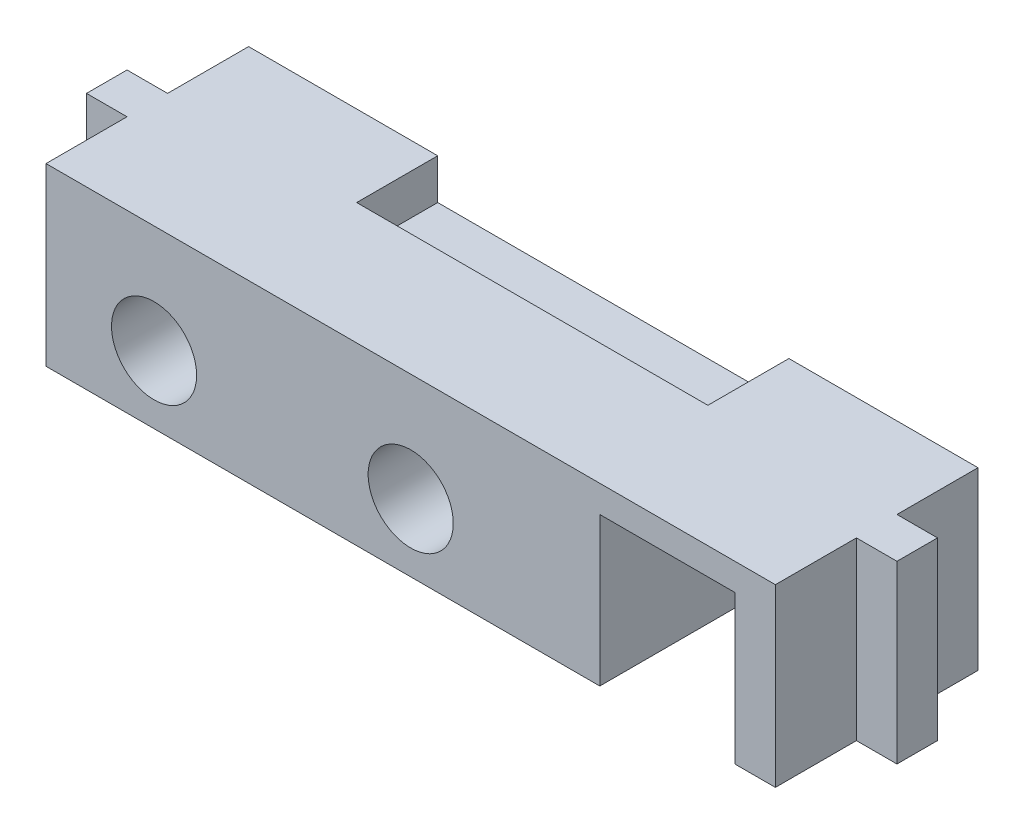
SolidWorks part; units mm, degrees
ref_plane "Front Plane" through (0, 0, 0) normal (0, 0, 1) x (1, 0, 0)
ref_plane "Top Plane" through (0, 0, 0) normal (0, 1, 0) x (1, 0, 0)
ref_plane "Right Plane" through (0, 0, 0) normal (1, 0, 0) x (0, 0, -1)
sketch "Sketch1" plane through (0, 0, 0) normal (0, 0, 1) x (1, 0, 0)
  line L0 (-19, 0) -> (19, 0) construction
  line L3 (-30, -5) -> (-30, 8)
  line L4 (-30, 8) -> (30, 8)
  line L5 (30, -5) -> (30, 8)
  line L6 (-17.2953, -10.5909) -> (25.0889, -10.5909)
  line L7 (-37.5889, -7) -> (12.4111, -7) construction
  line L8 (-37.5889, -7) -> (-37.5889, -5) construction
  line L9 (-37.5889, -5) -> (-13.75, -5) construction
  line L10 (12.4111, -7) -> (12.4111, -5) construction
  line L11 (-37.5889, -7) -> (12.4111, -5) construction
  line L12 (-37.5889, -5) -> (12.4111, -7) construction
  line L14 (14.5, -3) -> (23.5, -3) construction
  line L15 (14.5, -3) -> (14.5, 3) construction
  line L16 (14.5, 3) -> (23.5, 3) construction
  line L17 (23.5, -3) -> (23.5, 3) construction
  line L18 (14.5, -3) -> (23.5, 3) construction
  line L19 (14.5, 3) -> (23.5, -3) construction
  line L23 (-6.25, -5) -> (12.4111, -5) construction
  line L24 (-30, -5) -> (14, -5)
  line L34 (24, -5) -> (24, -6) construction
  line L35 (24, -6) -> (14, -6) construction
  line L36 (24, -5) -> (24, 6)
  line L37 (24, 6) -> (14, 6)
  line L38 (14, -5) -> (14, 6)
  line L39 (24, -6) -> (14, 6) construction
  line L40 (24, 6) -> (14, -6) construction
  line L41 (14, -6) -> (14, -5) construction
  line L42 (24, -5) -> (30, -5)
  circle A0 centre (0, 0) radius 10 construction
  circle A1 centre (19, 0) radius 9 construction
  circle A2 centre (-19, 0) radius 9 construction
  circle A3 centre (19, 0) radius 10.5909 construction
  circle A4 centre (-19, 0) radius 10.5909 construction
  circle A5 centre (0, 0) radius 1.5 construction
  circle A6 centre (-19, 0) radius 3.15
  circle A9 centre (0, 0) radius 3.15
  point P3 (0, 0)
  point P13 (0, 0)
  point P17 (0, 8)
  point P18 (-12.5889, -6)
  point P29 (3.8968, -10.5909)
  dimension "D1" = 20
  dimension "D2" = 18
  dimension "D5" = 3
  dimension "D6" = 10
  dimension "D9" = 6.3
  dimension "D3" = 13
  dimension "D4" = 2
  dimension "D7" = 9
  dimension "D8" = 6
  dimension "D11" = 8
  dimension "D12" = 60
  dimension "D14" = 12
extrude "Boss-Extrude1" add sketch "Sketch1" along normal mid plane 15
sketch "Sketch2" plane through (0, -5, 0) normal (0, -1, 0) x (1, 0, 0)
  line L0 (0, 0) -> (0, 7.5) construction
  line L1 (-10, -2) -> (-6, 2) construction
  line L6 (10, 2) -> (6, 2)
  line L7 (10, 2) -> (10, -2)
  line L12 (10, -2) -> (6, -2)
  line L13 (6, 2) -> (6, -2)
  line L14 (10, 2) -> (6, -2) construction
  line L15 (10, -2) -> (6, 2) construction
  line L16 (-30, 7.5) -> (14, 7.5) construction
  line L17 (-10, 2) -> (-6, -2) construction
  line L18 (-6, 2) -> (-6, -2)
  line L19 (-10, -2) -> (-6, -2)
  line L20 (-10, 2) -> (-10, -2)
  line L21 (-10, 2) -> (-6, 2)
  point P0 (8, 0)
  point P15 (-8, 0)
  dimension "D1" = 4
  dimension "D2" = 4
  dimension "D3" = 8
extrude "Boss-Extrude2" add sketch "Sketch2" along normal blind 2.5
sketch "Sketch3" plane through (0, 0, 0) normal (0, 0, 1) x (1, 0, 0)
  line L1 (-30, 8) -> (-27, 8)
  line L2 (-30, 8) -> (-30, -5)
  line L3 (-30, -5) -> (-27, -5)
  line L4 (-27, 8) -> (-27, -5)
  line L5 (-30, -5) -> (14, -5) construction
  line L6 (0, 0) -> (0, 6.25) construction
  line L7 (30, -5) -> (27, -5)
  line L8 (27, 8) -> (27, -5)
  line L9 (30, 8) -> (30, -5)
  line L10 (30, 8) -> (27, 8)
  dimension "D1" = 3
extrude "Cut-Extrude1" cut sketch "Sketch3" along normal blind 6 from surface at -7.5 starting at face at (3.15, 0, -7.5)
sketch "Sketch4" plane through (0, 0, 7.5) normal (0, 0, 1) x (1, 0, 0)
  line L0 (30, 8) -> (27, 8)
  line L1 (-30, 8) -> (30, 8) construction
  line L2 (27, 8) -> (27, -5)
  line L3 (24, -5) -> (30, -5) construction
  line L4 (27, -5) -> (30, -5)
  line L5 (30, -5) -> (30, 8)
  line L6 (0, 0.4036) -> (0, 8) construction
  line L7 (-30, -5) -> (-30, 8)
  line L8 (-27, -5) -> (-30, -5)
  line L9 (-27, 8) -> (-27, -5)
  line L10 (-30, 8) -> (-27, 8)
  dimension "D1" = 3
extrude "Cut-Extrude2" cut sketch "Sketch4" against normal blind 6
sketch "Sketch5" plane through (0, 0, -7.5) normal (0, 0, -1) x (-1, 0, 0)
  line L0 (0, 0) -> (0, 8) construction
  line L1 (27, 8) -> (-27, 8) construction
  line L2 (-13, 5) -> (-13, 8)
  line L3 (-13, 8) -> (13, 8)
  line L4 (-13, 5) -> (13, 5)
  line L5 (13, 5) -> (13, 8)
  point P9 (0, 5)
  dimension "D1" = 13
  dimension "D2" = 3
extrude "Cut-Extrude3" cut sketch "Sketch5" against normal blind 6
sketch "Sketch6" plane through (0, 0, -7.5) normal (0, 0, -1) x (-1, 0, 0)
  line L0 (-24, 3.4943) -> (-24, 6)
  line L2 (-24, 6) -> (-14, 6)
  line L3 (-14, 6) -> (-14, 3.4943)
  line L5 (-14, -5) -> (-14, 6) construction
  arc A1 (-14, 3.4943) -> (-17.9, 6) centre (-19, 0) ccw
  arc A2 (-20.1, 6) -> (-24, 3.4943) centre (-19, 0) ccw
extrude "Boss-Extrude3" add sketch "Sketch6" against normal blind 5.9
